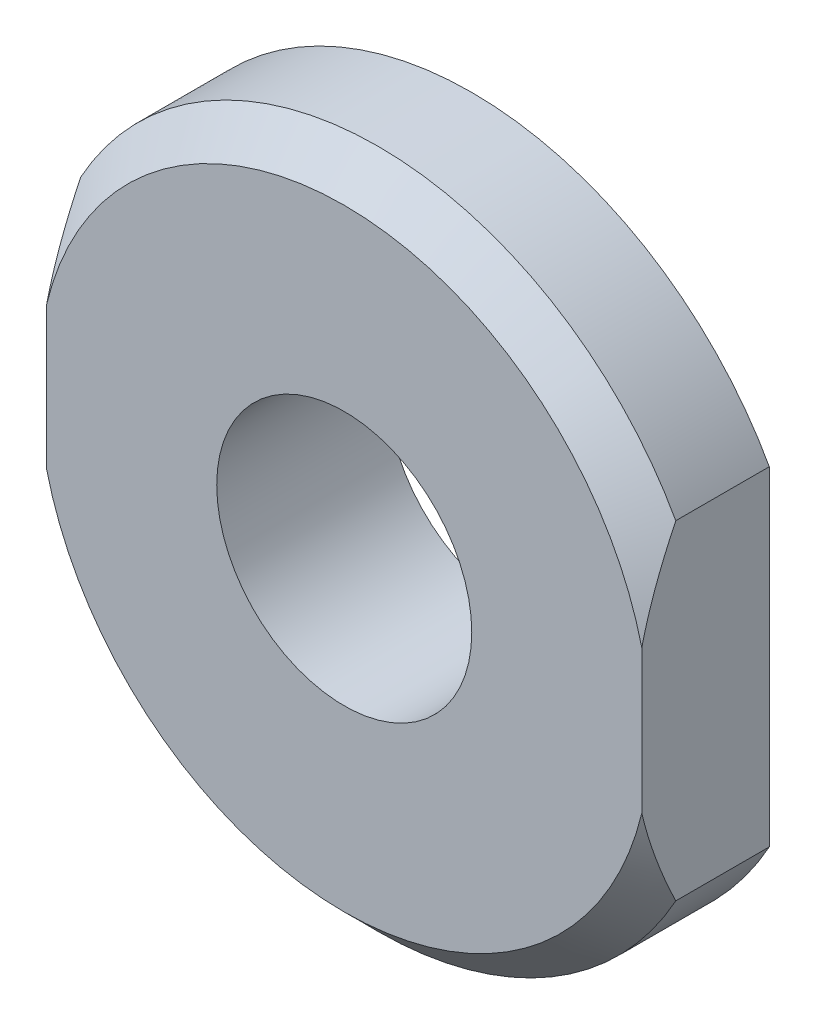
SolidWorks part; units mm, degrees
ref_plane "Front Plane" through (0, 0, 0) normal (0, 0, 1) x (1, 0, 0)
ref_plane "Top Plane" through (0, 0, 0) normal (0, 1, 0) x (1, 0, 0)
ref_plane "Right Plane" through (0, 0, 0) normal (1, 0, 0) x (0, 0, -1)
sketch "Sketch1" plane through (0, 0, 0) normal (0, 0, 1) x (1, 0, 0)
  line L0 (-3.5, 1.9365) -> (-3.5, -1.9365)
  line L1 (3.5, 1.9365) -> (3.5, -1.9365)
  arc A0 (-3.5, -1.9365) -> (3.5, -1.9365) centre (0, 0) ccw
  arc A1 (3.5, 1.9365) -> (-3.5, 1.9365) centre (0, 0) ccw
  point P6 (0, 0)
  point P7 (0, 0)
  point P8 (0, 0)
  point P9 (0, 0)
  point P10 (0, 0)
  point P11 (0, 0)
extrude "Boss-Extrude1" add sketch "Sketch1" along normal blind 1.5
sketch "Sketch3" plane through (0, 0, 0) normal (0, 0, -1) x (-1, 0, 0)
  circle A0 centre (0, 0) radius 2.5
extrude "Boss-Extrude2" add sketch "Sketch3" along normal blind 0.5
chamfer "Chamfer1" distance 0.4 angle 45 2 edges at (0, 4, 1.5) (0, -4, 1.5)
sketch "Sketch4" plane through (0, 0, 1.5) normal (0, 0, 1) x (1, 0, 0)
  point P0 (0, 0)
hole_wizard "Ø3.0mm Dowel Hole1" positions "Sketch4" profile "Sketch5" hole size "Ø3.0" standard "JIS" end condition through all
sketch "Sketch5" plane through (0, 0, 1.5) normal (1, 0, 0) x (0, -1, 0)
  line L0 (0, 0) -> (0, 2)
  line L1 (0, 2) -> (1.5, 2)
  line L2 (1.5, 2) -> (1.5, 0)
  line L5 (1.5, 0) -> (0, 0)
  line L11 (0, -6.35) -> (0, 107.95) construction
  dimension "Thru Hole Dia." = 3
  dimension "Thru Hole Depth" = 2
